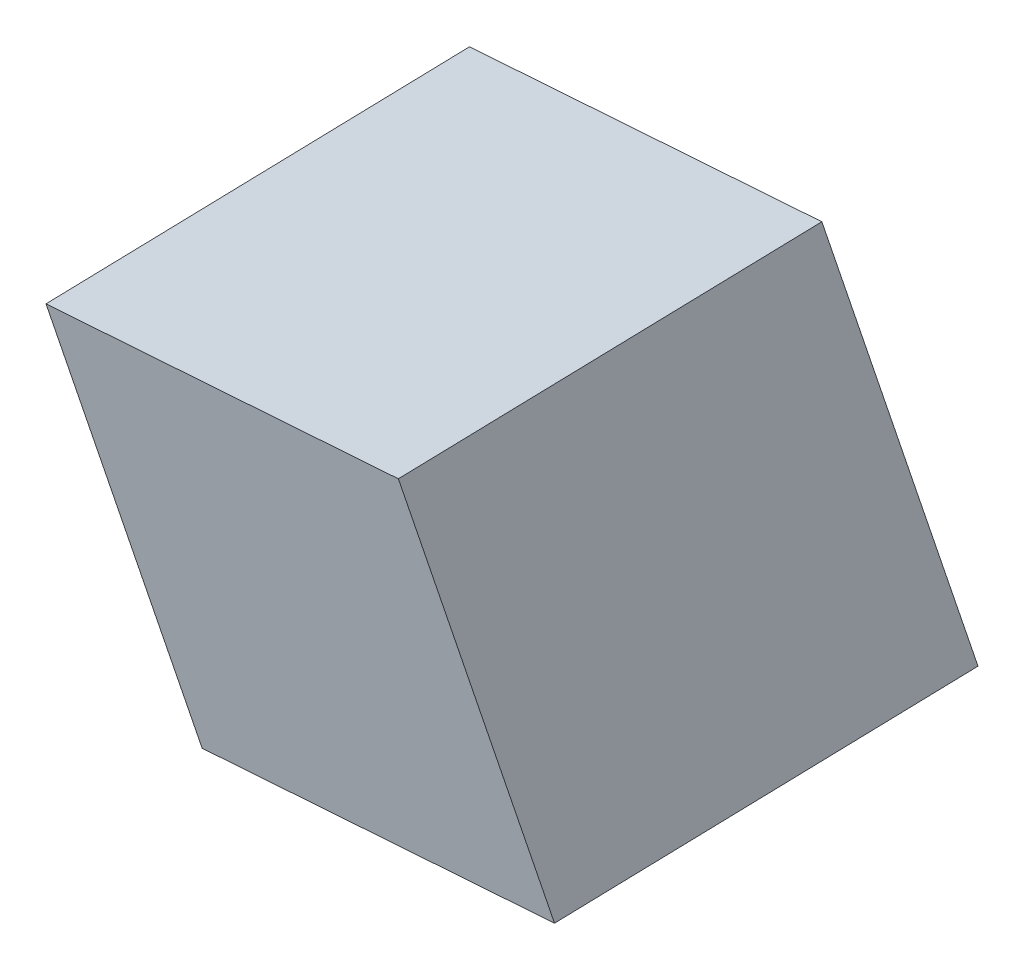
SolidWorks part; units mm, degrees
ref_plane "Спереди" through (0, 0, 0) normal (0, 0, 1) x (1, 0, 0)
ref_plane "Сверху" through (0, 0, 0) normal (0, 1, 0) x (1, 0, 0)
ref_plane "Справа" through (0, 0, 0) normal (1, 0, 0) x (0, 0, -1)
sketch "Эскиз1" plane through (-58.6345, 370.7631, -91.8707) normal (0.9475, 0.2508, 0.1984) x (0.2799, -0.9505, -0.1351)
  line L1 (-385.5602, -19.3583) -> (14.4398, -19.3583)
  line L2 (-385.5602, -19.3583) -> (-385.5602, 380.6417)
  line L3 (-385.5602, 380.6417) -> (14.4398, 380.6417)
  line L4 (14.4398, -19.3583) -> (14.4398, 380.6417)
  dimension "D1" = 400
  dimension "D2" = 400
extrude "Бобышка-Вытянуть1" add sketch "Эскиз1" against normal blind 500 contours L2 L3 L4 L1
